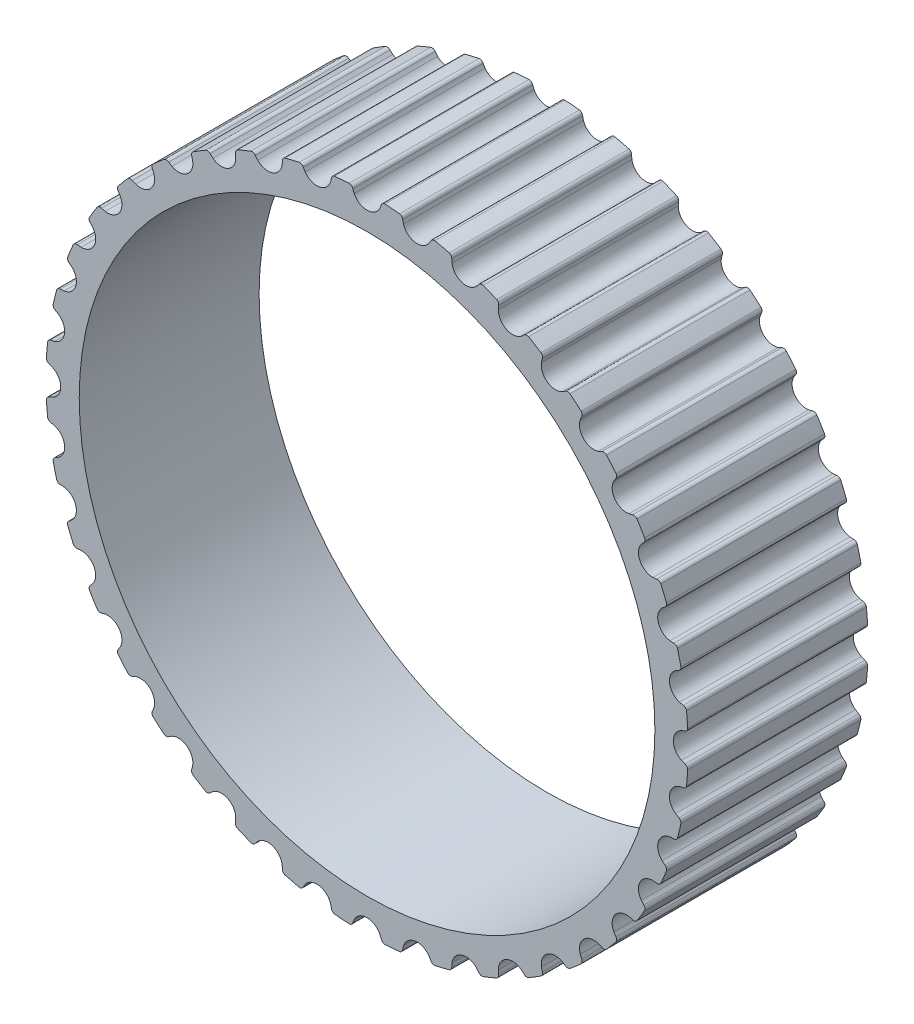
SolidWorks part; units mm, degrees
ref_plane "Piano frontale" through (0, 0, 0) normal (0, 0, 1) x (1, 0, 0)
ref_plane "Piano superiore" through (0, 0, 0) normal (0, 1, 0) x (1, 0, 0)
ref_plane "Piano destro" through (0, 0, 0) normal (1, 0, 0) x (0, 0, -1)
sketch "Schizzo1" plane through (0, 0, 0) normal (0, 0, 1) x (1, 0, 0)
  line L0 (0, 0) -> (0, 12.475) construction
  line L1 (0, 0) -> (0.4989, 12.2318) construction
  line L2 (0, 0) -> (1.2631, 12.4305) construction
  arc A0 (0.4989, 12.2318) -> (-0.4989, 12.2318) centre (0, 12.475) cw
  arc A1 (-0.4989, 12.2318) -> (-0.5539, 12.37) centre (0.4, 12.67) cw
  arc A2 (-0.5539, 12.37) -> (-0.697, 12.475) centre (-0.697, 12.325) ccw
  arc A3 (0.5539, 12.37) -> (0.697, 12.475) centre (0.697, 12.325) cw
  arc A4 (0.4989, 12.2318) -> (0.5539, 12.37) centre (-0.4, 12.67) ccw
  circle A5 centre (0, 0) radius 11.2
  arc A6 (2.4062, 12.0032) -> (1.4207, 12.1592) centre (1.9515, 12.3214) cw
  arc A7 (1.4207, 12.1592) -> (1.388, 12.3044) centre (2.3771, 12.4514) cw
  arc A8 (1.388, 12.3044) -> (1.2631, 12.4305) centre (1.2396, 12.2823) ccw
  arc A9 (2.4822, 12.131) -> (2.64, 12.2124) centre (2.6165, 12.0642) cw
  arc A10 (2.4062, 12.0032) -> (2.4822, 12.131) centre (1.5869, 12.5766) ccw
  arc A11 (4.2543, 11.479) -> (3.3054, 11.7873) centre (3.855, 11.8644) cw
  arc A12 (3.3054, 11.7873) -> (3.2957, 11.9357) centre (4.2957, 11.9263) cw
  arc A13 (3.2957, 11.9357) -> (3.1921, 12.0798) centre (3.1457, 11.9372) ccw
  arc A14 (4.3494, 11.5934) -> (4.5179, 11.649) centre (4.4715, 11.5064) cw
  arc A15 (4.2543, 11.479) -> (4.3494, 11.5934) centre (3.5348, 12.1735) ccw
  arc A16 (5.9976, 10.6721) -> (5.1086, 11.1251) centre (5.6635, 11.1153) cw
  arc A17 (5.1086, 11.1251) -> (5.1223, 11.2732) centre (6.1085, 11.1075) cw
  arc A18 (5.1223, 11.2732) -> (5.0425, 11.4318) centre (4.9744, 11.2981) ccw
  arc A19 (6.1094, 10.7703) -> (6.2846, 10.7989) centre (6.2165, 10.6652) cw
  arc A20 (5.9976, 10.6721) -> (6.1094, 10.7703) centre (5.3957, 11.4706) ccw
  arc A21 (7.5933, 9.6025) -> (6.7861, 10.189) centre (7.3326, 10.0925) cw
  arc A22 (6.7861, 10.189) -> (6.8228, 10.3331) centre (7.7708, 10.0151) cw
  arc A23 (6.8228, 10.3331) -> (6.7687, 10.5022) centre (6.6805, 10.3808) ccw
  arc A24 (7.719, 9.6819) -> (7.8965, 9.6828) centre (7.8084, 9.5614) cw
  arc A25 (7.5933, 9.6025) -> (7.719, 9.6819) centre (7.1236, 10.4854) ccw
  arc A26 (9.0019, 8.2964) -> (8.2964, 9.0019) centre (8.8212, 8.8212) cw
  arc A27 (8.2964, 9.0019) -> (8.3552, 9.1386) centre (9.2419, 8.6762) cw
  arc A28 (8.3552, 9.1386) -> (8.3283, 9.314) centre (8.2222, 9.208) ccw
  arc A29 (9.1386, 8.3552) -> (9.314, 8.3283) centre (9.208, 8.2222) cw
  arc A30 (9.0019, 8.2964) -> (9.1386, 8.3552) centre (8.6762, 9.2419) ccw
  arc A31 (10.189, 6.7861) -> (9.6025, 7.5933) centre (10.0925, 7.3326) cw
  arc A32 (9.6025, 7.5933) -> (9.6819, 7.719) centre (10.4854, 7.1236) cw
  arc A33 (9.6819, 7.719) -> (9.6828, 7.8965) centre (9.5614, 7.8084) ccw
  arc A34 (10.3331, 6.8228) -> (10.5022, 6.7687) centre (10.3808, 6.6805) cw
  arc A35 (10.189, 6.7861) -> (10.3331, 6.8228) centre (10.0151, 7.7708) ccw
  arc A36 (11.1251, 5.1086) -> (10.6721, 5.9976) centre (11.1153, 5.6635) cw
  arc A37 (10.6721, 5.9976) -> (10.7703, 6.1094) centre (11.4706, 5.3957) cw
  arc A38 (10.7703, 6.1094) -> (10.7989, 6.2846) centre (10.6652, 6.2165) ccw
  arc A39 (11.2732, 5.1223) -> (11.4318, 5.0425) centre (11.2981, 4.9744) cw
  arc A40 (11.1251, 5.1086) -> (11.2732, 5.1223) centre (11.1075, 6.1085) ccw
  arc A41 (11.7873, 3.3054) -> (11.479, 4.2543) centre (11.8644, 3.855) cw
  arc A42 (11.479, 4.2543) -> (11.5934, 4.3494) centre (12.1735, 3.5348) cw
  arc A43 (11.5934, 4.3494) -> (11.649, 4.5179) centre (11.5064, 4.4715) ccw
  arc A44 (11.9357, 3.2957) -> (12.0798, 3.1921) centre (11.9372, 3.1457) cw
  arc A45 (11.7873, 3.3054) -> (11.9357, 3.2957) centre (11.9263, 4.2957) ccw
  arc A46 (12.1592, 1.4207) -> (12.0032, 2.4062) centre (12.3214, 1.9515) cw
  arc A47 (12.0032, 2.4062) -> (12.131, 2.4822) centre (12.5766, 1.5869) cw
  arc A48 (12.131, 2.4822) -> (12.2124, 2.64) centre (12.0642, 2.6165) ccw
  arc A49 (12.3044, 1.388) -> (12.4305, 1.2631) centre (12.2823, 1.2396) cw
  arc A50 (12.1592, 1.4207) -> (12.3044, 1.388) centre (12.4514, 2.3771) ccw
  arc A51 (12.2318, -0.4989) -> (12.2318, 0.4989) centre (12.475, 0) cw
  arc A52 (12.2318, 0.4989) -> (12.37, 0.5539) centre (12.67, -0.4) cw
  arc A53 (12.37, 0.5539) -> (12.475, 0.697) centre (12.325, 0.697) ccw
  arc A54 (12.37, -0.5539) -> (12.475, -0.697) centre (12.325, -0.697) cw
  arc A55 (12.2318, -0.4989) -> (12.37, -0.5539) centre (12.67, 0.4) ccw
  arc A56 (12.0032, -2.4062) -> (12.1592, -1.4207) centre (12.3214, -1.9515) cw
  arc A57 (12.1592, -1.4207) -> (12.3044, -1.388) centre (12.4514, -2.3771) cw
  arc A58 (12.3044, -1.388) -> (12.4305, -1.2631) centre (12.2823, -1.2396) ccw
  arc A59 (12.131, -2.4822) -> (12.2124, -2.64) centre (12.0642, -2.6165) cw
  arc A60 (12.0032, -2.4062) -> (12.131, -2.4822) centre (12.5766, -1.5869) ccw
  arc A61 (11.479, -4.2543) -> (11.7873, -3.3054) centre (11.8644, -3.855) cw
  arc A62 (11.7873, -3.3054) -> (11.9357, -3.2957) centre (11.9263, -4.2957) cw
  arc A63 (11.9357, -3.2957) -> (12.0798, -3.1921) centre (11.9372, -3.1457) ccw
  arc A64 (11.5934, -4.3494) -> (11.649, -4.5179) centre (11.5064, -4.4715) cw
  arc A65 (11.479, -4.2543) -> (11.5934, -4.3494) centre (12.1735, -3.5348) ccw
  arc A66 (10.6721, -5.9976) -> (11.1251, -5.1086) centre (11.1153, -5.6635) cw
  arc A67 (11.1251, -5.1086) -> (11.2732, -5.1223) centre (11.1075, -6.1085) cw
  arc A68 (11.2732, -5.1223) -> (11.4318, -5.0425) centre (11.2981, -4.9744) ccw
  arc A69 (10.7703, -6.1094) -> (10.7989, -6.2846) centre (10.6652, -6.2165) cw
  arc A70 (10.6721, -5.9976) -> (10.7703, -6.1094) centre (11.4706, -5.3957) ccw
  arc A71 (9.6025, -7.5933) -> (10.189, -6.7861) centre (10.0925, -7.3326) cw
  arc A72 (10.189, -6.7861) -> (10.3331, -6.8228) centre (10.0151, -7.7708) cw
  arc A73 (10.3331, -6.8228) -> (10.5022, -6.7687) centre (10.3808, -6.6805) ccw
  arc A74 (9.6819, -7.719) -> (9.6828, -7.8965) centre (9.5614, -7.8084) cw
  arc A75 (9.6025, -7.5933) -> (9.6819, -7.719) centre (10.4854, -7.1236) ccw
  arc A76 (8.2964, -9.0019) -> (9.0019, -8.2964) centre (8.8212, -8.8212) cw
  arc A77 (9.0019, -8.2964) -> (9.1386, -8.3552) centre (8.6762, -9.2419) cw
  arc A78 (9.1386, -8.3552) -> (9.314, -8.3283) centre (9.208, -8.2222) ccw
  arc A79 (8.3552, -9.1386) -> (8.3283, -9.314) centre (8.2222, -9.208) cw
  arc A80 (8.2964, -9.0019) -> (8.3552, -9.1386) centre (9.2419, -8.6762) ccw
  arc A81 (6.7861, -10.189) -> (7.5933, -9.6025) centre (7.3326, -10.0925) cw
  arc A82 (7.5933, -9.6025) -> (7.719, -9.6819) centre (7.1236, -10.4854) cw
  arc A83 (7.719, -9.6819) -> (7.8965, -9.6828) centre (7.8084, -9.5614) ccw
  arc A84 (6.8228, -10.3331) -> (6.7687, -10.5022) centre (6.6805, -10.3808) cw
  arc A85 (6.7861, -10.189) -> (6.8228, -10.3331) centre (7.7708, -10.0151) ccw
  arc A86 (5.1086, -11.1251) -> (5.9976, -10.6721) centre (5.6635, -11.1153) cw
  arc A87 (5.9976, -10.6721) -> (6.1094, -10.7703) centre (5.3957, -11.4706) cw
  arc A88 (6.1094, -10.7703) -> (6.2846, -10.7989) centre (6.2165, -10.6652) ccw
  arc A89 (5.1223, -11.2732) -> (5.0425, -11.4318) centre (4.9744, -11.2981) cw
  arc A90 (5.1086, -11.1251) -> (5.1223, -11.2732) centre (6.1085, -11.1075) ccw
  arc A91 (3.3054, -11.7873) -> (4.2543, -11.479) centre (3.855, -11.8644) cw
  arc A92 (4.2543, -11.479) -> (4.3494, -11.5934) centre (3.5348, -12.1735) cw
  arc A93 (4.3494, -11.5934) -> (4.5179, -11.649) centre (4.4715, -11.5064) ccw
  arc A94 (3.2957, -11.9357) -> (3.1921, -12.0798) centre (3.1457, -11.9372) cw
  arc A95 (3.3054, -11.7873) -> (3.2957, -11.9357) centre (4.2957, -11.9263) ccw
  arc A96 (1.4207, -12.1592) -> (2.4062, -12.0032) centre (1.9515, -12.3214) cw
  arc A97 (2.4062, -12.0032) -> (2.4822, -12.131) centre (1.5869, -12.5766) cw
  arc A98 (2.4822, -12.131) -> (2.64, -12.2124) centre (2.6165, -12.0642) ccw
  arc A99 (1.388, -12.3044) -> (1.2631, -12.4305) centre (1.2396, -12.2823) cw
  arc A100 (1.4207, -12.1592) -> (1.388, -12.3044) centre (2.3771, -12.4514) ccw
  arc A101 (-0.4989, -12.2318) -> (0.4989, -12.2318) centre (0, -12.475) cw
  arc A102 (0.4989, -12.2318) -> (0.5539, -12.37) centre (-0.4, -12.67) cw
  arc A103 (0.5539, -12.37) -> (0.697, -12.475) centre (0.697, -12.325) ccw
  arc A104 (-0.5539, -12.37) -> (-0.697, -12.475) centre (-0.697, -12.325) cw
  arc A105 (-0.4989, -12.2318) -> (-0.5539, -12.37) centre (0.4, -12.67) ccw
  arc A106 (-2.4062, -12.0032) -> (-1.4207, -12.1592) centre (-1.9515, -12.3214) cw
  arc A107 (-1.4207, -12.1592) -> (-1.388, -12.3044) centre (-2.3771, -12.4514) cw
  arc A108 (-1.388, -12.3044) -> (-1.2631, -12.4305) centre (-1.2396, -12.2823) ccw
  arc A109 (-2.4822, -12.131) -> (-2.64, -12.2124) centre (-2.6165, -12.0642) cw
  arc A110 (-2.4062, -12.0032) -> (-2.4822, -12.131) centre (-1.5869, -12.5766) ccw
  arc A111 (-4.2543, -11.479) -> (-3.3054, -11.7873) centre (-3.855, -11.8644) cw
  arc A112 (-3.3054, -11.7873) -> (-3.2957, -11.9357) centre (-4.2957, -11.9263) cw
  arc A113 (-3.2957, -11.9357) -> (-3.1921, -12.0798) centre (-3.1457, -11.9372) ccw
  arc A114 (-4.3494, -11.5934) -> (-4.5179, -11.649) centre (-4.4715, -11.5064) cw
  arc A115 (-4.2543, -11.479) -> (-4.3494, -11.5934) centre (-3.5348, -12.1735) ccw
  arc A116 (-5.9976, -10.6721) -> (-5.1086, -11.1251) centre (-5.6635, -11.1153) cw
  arc A117 (-5.1086, -11.1251) -> (-5.1223, -11.2732) centre (-6.1085, -11.1075) cw
  arc A118 (-5.1223, -11.2732) -> (-5.0425, -11.4318) centre (-4.9744, -11.2981) ccw
  arc A119 (-6.1094, -10.7703) -> (-6.2846, -10.7989) centre (-6.2165, -10.6652) cw
  arc A120 (-5.9976, -10.6721) -> (-6.1094, -10.7703) centre (-5.3957, -11.4706) ccw
  arc A121 (-7.5933, -9.6025) -> (-6.7861, -10.189) centre (-7.3326, -10.0925) cw
  arc A122 (-6.7861, -10.189) -> (-6.8228, -10.3331) centre (-7.7708, -10.0151) cw
  arc A123 (-6.8228, -10.3331) -> (-6.7687, -10.5022) centre (-6.6805, -10.3808) ccw
  arc A124 (-7.719, -9.6819) -> (-7.8965, -9.6828) centre (-7.8084, -9.5614) cw
  arc A125 (-7.5933, -9.6025) -> (-7.719, -9.6819) centre (-7.1236, -10.4854) ccw
  arc A126 (-9.0019, -8.2964) -> (-8.2964, -9.0019) centre (-8.8212, -8.8212) cw
  arc A127 (-8.2964, -9.0019) -> (-8.3552, -9.1386) centre (-9.2419, -8.6762) cw
  arc A128 (-8.3552, -9.1386) -> (-8.3283, -9.314) centre (-8.2222, -9.208) ccw
  arc A129 (-9.1386, -8.3552) -> (-9.314, -8.3283) centre (-9.208, -8.2222) cw
  arc A130 (-9.0019, -8.2964) -> (-9.1386, -8.3552) centre (-8.6762, -9.2419) ccw
  arc A131 (-10.189, -6.7861) -> (-9.6025, -7.5933) centre (-10.0925, -7.3326) cw
  arc A132 (-9.6025, -7.5933) -> (-9.6819, -7.719) centre (-10.4854, -7.1236) cw
  arc A133 (-9.6819, -7.719) -> (-9.6828, -7.8965) centre (-9.5614, -7.8084) ccw
  arc A134 (-10.3331, -6.8228) -> (-10.5022, -6.7687) centre (-10.3808, -6.6805) cw
  arc A135 (-10.189, -6.7861) -> (-10.3331, -6.8228) centre (-10.0151, -7.7708) ccw
  arc A136 (-11.1251, -5.1086) -> (-10.6721, -5.9976) centre (-11.1153, -5.6635) cw
  arc A137 (-10.6721, -5.9976) -> (-10.7703, -6.1094) centre (-11.4706, -5.3957) cw
  arc A138 (-10.7703, -6.1094) -> (-10.7989, -6.2846) centre (-10.6652, -6.2165) ccw
  arc A139 (-11.2732, -5.1223) -> (-11.4318, -5.0425) centre (-11.2981, -4.9744) cw
  arc A140 (-11.1251, -5.1086) -> (-11.2732, -5.1223) centre (-11.1075, -6.1085) ccw
  arc A141 (-11.7873, -3.3054) -> (-11.479, -4.2543) centre (-11.8644, -3.855) cw
  arc A142 (-11.479, -4.2543) -> (-11.5934, -4.3494) centre (-12.1735, -3.5348) cw
  arc A143 (-11.5934, -4.3494) -> (-11.649, -4.5179) centre (-11.5064, -4.4715) ccw
  arc A144 (-11.9357, -3.2957) -> (-12.0798, -3.1921) centre (-11.9372, -3.1457) cw
  arc A145 (-11.7873, -3.3054) -> (-11.9357, -3.2957) centre (-11.9263, -4.2957) ccw
  arc A146 (-12.1592, -1.4207) -> (-12.0032, -2.4062) centre (-12.3214, -1.9515) cw
  arc A147 (-12.0032, -2.4062) -> (-12.131, -2.4822) centre (-12.5766, -1.5869) cw
  arc A148 (-12.131, -2.4822) -> (-12.2124, -2.64) centre (-12.0642, -2.6165) ccw
  arc A149 (-12.3044, -1.388) -> (-12.4305, -1.2631) centre (-12.2823, -1.2396) cw
  arc A150 (-12.1592, -1.4207) -> (-12.3044, -1.388) centre (-12.4514, -2.3771) ccw
  arc A151 (-12.2318, 0.4989) -> (-12.2318, -0.4989) centre (-12.475, 0) cw
  arc A152 (-12.2318, -0.4989) -> (-12.37, -0.5539) centre (-12.67, 0.4) cw
  arc A153 (-12.37, -0.5539) -> (-12.475, -0.697) centre (-12.325, -0.697) ccw
  arc A154 (-12.37, 0.5539) -> (-12.475, 0.697) centre (-12.325, 0.697) cw
  arc A155 (-12.2318, 0.4989) -> (-12.37, 0.5539) centre (-12.67, -0.4) ccw
  arc A156 (-12.0032, 2.4062) -> (-12.1592, 1.4207) centre (-12.3214, 1.9515) cw
  arc A157 (-12.1592, 1.4207) -> (-12.3044, 1.388) centre (-12.4514, 2.3771) cw
  arc A158 (-12.3044, 1.388) -> (-12.4305, 1.2631) centre (-12.2823, 1.2396) ccw
  arc A159 (-12.131, 2.4822) -> (-12.2124, 2.64) centre (-12.0642, 2.6165) cw
  arc A160 (-12.0032, 2.4062) -> (-12.131, 2.4822) centre (-12.5766, 1.5869) ccw
  arc A161 (-11.479, 4.2543) -> (-11.7873, 3.3054) centre (-11.8644, 3.855) cw
  arc A162 (-11.7873, 3.3054) -> (-11.9357, 3.2957) centre (-11.9263, 4.2957) cw
  arc A163 (-11.9357, 3.2957) -> (-12.0798, 3.1921) centre (-11.9372, 3.1457) ccw
  arc A164 (-11.5934, 4.3494) -> (-11.649, 4.5179) centre (-11.5064, 4.4715) cw
  arc A165 (-11.479, 4.2543) -> (-11.5934, 4.3494) centre (-12.1735, 3.5348) ccw
  arc A166 (-10.6721, 5.9976) -> (-11.1251, 5.1086) centre (-11.1153, 5.6635) cw
  arc A167 (-11.1251, 5.1086) -> (-11.2732, 5.1223) centre (-11.1075, 6.1085) cw
  arc A168 (-11.2732, 5.1223) -> (-11.4318, 5.0425) centre (-11.2981, 4.9744) ccw
  arc A169 (-10.7703, 6.1094) -> (-10.7989, 6.2846) centre (-10.6652, 6.2165) cw
  arc A170 (-10.6721, 5.9976) -> (-10.7703, 6.1094) centre (-11.4706, 5.3957) ccw
  arc A171 (-9.6025, 7.5933) -> (-10.189, 6.7861) centre (-10.0925, 7.3326) cw
  arc A172 (-10.189, 6.7861) -> (-10.3331, 6.8228) centre (-10.0151, 7.7708) cw
  arc A173 (-10.3331, 6.8228) -> (-10.5022, 6.7687) centre (-10.3808, 6.6805) ccw
  arc A174 (-9.6819, 7.719) -> (-9.6828, 7.8965) centre (-9.5614, 7.8084) cw
  arc A175 (-9.6025, 7.5933) -> (-9.6819, 7.719) centre (-10.4854, 7.1236) ccw
  arc A176 (-8.2964, 9.0019) -> (-9.0019, 8.2964) centre (-8.8212, 8.8212) cw
  arc A177 (-9.0019, 8.2964) -> (-9.1386, 8.3552) centre (-8.6762, 9.2419) cw
  arc A178 (-9.1386, 8.3552) -> (-9.314, 8.3283) centre (-9.208, 8.2222) ccw
  arc A179 (-8.3552, 9.1386) -> (-8.3283, 9.314) centre (-8.2222, 9.208) cw
  arc A180 (-8.2964, 9.0019) -> (-8.3552, 9.1386) centre (-9.2419, 8.6762) ccw
  arc A181 (-6.7861, 10.189) -> (-7.5933, 9.6025) centre (-7.3326, 10.0925) cw
  arc A182 (-7.5933, 9.6025) -> (-7.719, 9.6819) centre (-7.1236, 10.4854) cw
  arc A183 (-7.719, 9.6819) -> (-7.8965, 9.6828) centre (-7.8084, 9.5614) ccw
  arc A184 (-6.8228, 10.3331) -> (-6.7687, 10.5022) centre (-6.6805, 10.3808) cw
  arc A185 (-6.7861, 10.189) -> (-6.8228, 10.3331) centre (-7.7708, 10.0151) ccw
  arc A186 (-5.1086, 11.1251) -> (-5.9976, 10.6721) centre (-5.6635, 11.1153) cw
  arc A187 (-5.9976, 10.6721) -> (-6.1094, 10.7703) centre (-5.3957, 11.4706) cw
  arc A188 (-6.1094, 10.7703) -> (-6.2846, 10.7989) centre (-6.2165, 10.6652) ccw
  arc A189 (-5.1223, 11.2732) -> (-5.0425, 11.4318) centre (-4.9744, 11.2981) cw
  arc A190 (-5.1086, 11.1251) -> (-5.1223, 11.2732) centre (-6.1085, 11.1075) ccw
  arc A191 (-3.3054, 11.7873) -> (-4.2543, 11.479) centre (-3.855, 11.8644) cw
  arc A192 (-4.2543, 11.479) -> (-4.3494, 11.5934) centre (-3.5348, 12.1735) cw
  arc A193 (-4.3494, 11.5934) -> (-4.5179, 11.649) centre (-4.4715, 11.5064) ccw
  arc A194 (-3.2957, 11.9357) -> (-3.1921, 12.0798) centre (-3.1457, 11.9372) cw
  arc A195 (-3.3054, 11.7873) -> (-3.2957, 11.9357) centre (-4.2957, 11.9263) ccw
  arc A196 (-1.4207, 12.1592) -> (-2.4062, 12.0032) centre (-1.9515, 12.3214) cw
  arc A197 (-2.4062, 12.0032) -> (-2.4822, 12.131) centre (-1.5869, 12.5766) cw
  arc A198 (-2.4822, 12.131) -> (-2.64, 12.2124) centre (-2.6165, 12.0642) ccw
  arc A199 (-1.388, 12.3044) -> (-1.2631, 12.4305) centre (-1.2396, 12.2823) cw
  arc A200 (-1.4207, 12.1592) -> (-1.388, 12.3044) centre (-2.3771, 12.4514) ccw
  arc A201 (0.697, 12.475) -> (1.2631, 12.4305) centre (0, 0) cw
  arc A202 (2.64, 12.2124) -> (3.1921, 12.0798) centre (0, 0) cw
  arc A203 (4.5179, 11.649) -> (5.0425, 11.4318) centre (0, 0) cw
  arc A204 (6.2846, 10.7989) -> (6.7687, 10.5022) centre (0, 0) cw
  arc A205 (7.8965, 9.6828) -> (8.3283, 9.314) centre (0, 0) cw
  arc A206 (9.314, 8.3283) -> (9.6828, 7.8965) centre (0, 0) cw
  arc A207 (10.5022, 6.7687) -> (10.7989, 6.2846) centre (0, 0) cw
  arc A208 (11.4318, 5.0425) -> (11.649, 4.5179) centre (0, 0) cw
  arc A209 (12.0798, 3.1921) -> (12.2124, 2.64) centre (0, 0) cw
  arc A210 (12.4305, 1.2631) -> (12.475, 0.697) centre (0, 0) cw
  arc A211 (12.475, -0.697) -> (12.4305, -1.2631) centre (0, 0) cw
  arc A212 (12.2124, -2.64) -> (12.0798, -3.1921) centre (0, 0) cw
  arc A213 (11.649, -4.5179) -> (11.4318, -5.0425) centre (0, 0) cw
  arc A214 (10.7989, -6.2846) -> (10.5022, -6.7687) centre (0, 0) cw
  arc A215 (9.6828, -7.8965) -> (9.314, -8.3283) centre (0, 0) cw
  arc A216 (8.3283, -9.314) -> (7.8965, -9.6828) centre (0, 0) cw
  arc A217 (6.7687, -10.5022) -> (6.2846, -10.7989) centre (0, 0) cw
  arc A218 (5.0425, -11.4318) -> (4.5179, -11.649) centre (0, 0) cw
  arc A219 (3.1921, -12.0798) -> (2.64, -12.2124) centre (0, 0) cw
  arc A220 (1.2631, -12.4305) -> (0.697, -12.475) centre (0, 0) cw
  arc A221 (-0.697, -12.475) -> (-1.2631, -12.4305) centre (0, 0) cw
  arc A222 (-2.64, -12.2124) -> (-3.1921, -12.0798) centre (0, 0) cw
  arc A223 (-4.5179, -11.649) -> (-5.0425, -11.4318) centre (0, 0) cw
  arc A224 (-6.2846, -10.7989) -> (-6.7687, -10.5022) centre (0, 0) cw
  arc A225 (-7.8965, -9.6828) -> (-8.3283, -9.314) centre (0, 0) cw
  arc A226 (-9.314, -8.3283) -> (-9.6828, -7.8965) centre (0, 0) cw
  arc A227 (-10.5022, -6.7687) -> (-10.7989, -6.2846) centre (0, 0) cw
  arc A228 (-11.4318, -5.0425) -> (-11.649, -4.5179) centre (0, 0) cw
  arc A229 (-12.0798, -3.1921) -> (-12.2124, -2.64) centre (0, 0) cw
  arc A230 (-12.4305, -1.2631) -> (-12.475, -0.697) centre (0, 0) cw
  arc A231 (-12.475, 0.697) -> (-12.4305, 1.2631) centre (0, 0) cw
  arc A232 (-12.2124, 2.64) -> (-12.0798, 3.1921) centre (0, 0) cw
  arc A233 (-11.649, 4.5179) -> (-11.4318, 5.0425) centre (0, 0) cw
  arc A234 (-10.7989, 6.2846) -> (-10.5022, 6.7687) centre (0, 0) cw
  arc A235 (-9.6828, 7.8965) -> (-9.314, 8.3283) centre (0, 0) cw
  arc A236 (-8.3283, 9.314) -> (-7.8965, 9.6828) centre (0, 0) cw
  arc A237 (-6.7687, 10.5022) -> (-6.2846, 10.7989) centre (0, 0) cw
  arc A238 (-5.0425, 11.4318) -> (-4.5179, 11.649) centre (0, 0) cw
  arc A239 (-3.1921, 12.0798) -> (-2.64, 12.2124) centre (0, 0) cw
  arc A240 (-1.2631, 12.4305) -> (-0.697, 12.475) centre (0, 0) cw
  point P6 (0.4, 12.67)
  point P16 (-2.0935, 14.2206)
  point P20 (2.3771, 12.4514)
  point P32 (4.2957, 11.9263)
  point P44 (6.1085, 11.1075)
  point P56 (7.7708, 10.0151)
  point P68 (9.2419, 8.6762)
  point P80 (10.4854, 7.1236)
  point P92 (11.4706, 5.3957)
  point P104 (12.1735, 3.5348)
  point P116 (12.5766, 1.5869)
  point P128 (12.67, -0.4)
  point P140 (12.4514, -2.3771)
  point P152 (11.9263, -4.2957)
  point P164 (11.1075, -6.1085)
  point P176 (10.0151, -7.7708)
  point P188 (8.6762, -9.2419)
  point P200 (7.1236, -10.4854)
  point P212 (5.3957, -11.4706)
  point P224 (3.5348, -12.1735)
  point P236 (1.5869, -12.5766)
  point P248 (-0.4, -12.67)
  point P260 (-2.3771, -12.4514)
  point P272 (-4.2957, -11.9263)
  point P284 (-6.1085, -11.1075)
  point P296 (-7.7708, -10.0151)
  point P308 (-9.2419, -8.6762)
  point P320 (-10.4854, -7.1236)
  point P332 (-11.4706, -5.3957)
  point P344 (-12.1735, -3.5348)
  point P356 (-12.5766, -1.5869)
  point P368 (-12.67, 0.4)
  point P380 (-12.4514, 2.3771)
  point P392 (-11.9263, 4.2957)
  point P404 (-11.1075, 6.1085)
  point P416 (-10.0151, 7.7708)
  point P428 (-8.6762, 9.2419)
  point P440 (-7.1236, 10.4854)
  point P452 (-5.3957, 11.4706)
  point P464 (-3.5348, 12.1735)
  point P476 (-1.5869, 12.5766)
  dimension "D5" = 22.4
  dimension "D10" = 12.4945
  dimension "D7" = 40
  dimension "D9" = 40
extrude "Estrusione-Estrusione1" add sketch "Schizzo1" along normal mid plane 7
